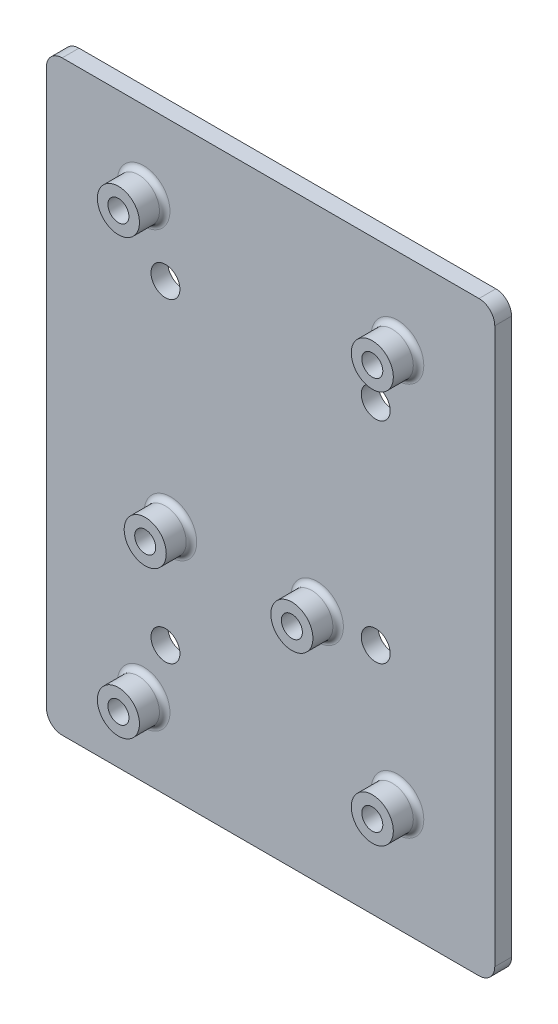
SolidWorks part; units mm, degrees
ref_plane "Front Plane" through (0, 0, 0) normal (0, 0, 1) x (1, 0, 0)
ref_plane "Top Plane" through (0, 0, 0) normal (0, 1, 0) x (1, 0, 0)
ref_plane "Right Plane" through (0, 0, 0) normal (1, 0, 0) x (0, 0, -1)
sketch "Sketch1" plane through (0, 0, 0) normal (0, 0, 1) x (1, 0, 0)
  line L0 (0, 0) -> (27.9, 0) construction
  line L1 (-5.1, 52) -> (43.2, 52) construction
  line L2 (43.2, 52) -> (45.7, 52) construction
  line L3 (27.9, 0) -> (27.9, -24.1) construction
  line L4 (27.9, -24.1) -> (43.2, -24.1) construction
  line L5 (0, 0) -> (0, -30.6) construction
  line L6 (0, -30.6) -> (-5.1, -30.6) construction
  line L7 (-7.6, 66) -> (45.7, 66)
  line L8 (45.7, 66) -> (45.7, -31.4737)
  line L9 (30.4, -35.6) -> (-2.6, -35.6) construction
  line L10 (-7.6, -33.1) -> (-7.6, 66)
  line L11 (-5.1, 52) -> (-5.1, -30.6) construction
  line L12 (43.2, -24.1) -> (43.2, 52) construction
  line L13 (-5.1, 52) -> (-7.6, 52) construction
  line L14 (-7.6, -33.1) -> (-5.1, -33.1)
  line L15 (-5.1, -33.1) -> (-2.6, -35.6)
  line L16 (-2.6, -35.6) -> (30.4, -35.6)
  line L17 (30.4, -35.6) -> (32.9, -33.1)
  line L18 (32.9, -33.1) -> (44.0737, -33.1)
  line L19 (44.0737, -33.1) -> (45.7, -31.4737)
  line L20 (-23.6, 67) -> (61.7, 67)
  line L21 (61.7, 67) -> (61.7, -44.6)
  line L22 (61.7, -44.6) -> (-23.6, -44.6)
  line L23 (-23.6, -44.6) -> (-23.6, 67)
  circle A0 centre (-5.1, 52) radius 2
  circle A1 centre (43.2, 50.7) radius 2
  circle A2 centre (0, 0) radius 2
  circle A3 centre (27.9, 0) radius 2
  circle A4 centre (-5.1, -30.6) radius 2
  circle A5 centre (43.2, -24.1) radius 2
  point P9 (43.2, 50.7)
  dimension "D11" = 4
  dimension "D17" = 1.3
  dimension "D22" = 4
  dimension "D23" = 4
  dimension "D1" = 53.3
  dimension "D2" = 101.6
  dimension "D3" = 14
  dimension "D4" = 2.5
  dimension "D5" = 5.1
  dimension "D6" = 2.5
  dimension "D7" = 24.1
  dimension "D8" = 52
  dimension "D9" = 27.9
  dimension "D10" = 5
  dimension "D12" = 5
  dimension "D13" = 45
  dimension "D14" = 2.5
  dimension "D15" = 33
  dimension "D16" = 2.3
  dimension "D18" = 1
  dimension "D19" = 16
  dimension "D20" = 16
  dimension "D21" = 9
extrude "Base Plate" add sketch "Sketch1" along normal blind 3.2 contours L18 L19 L8 L7 L10 L14 L15 L16 L17 A5 A4 A3 A2 A1 A0 | L23 L22 L21 L20 L19 L18 L17 L16 L15 L14 L10 L7 L8
sketch "Sketch2" plane through (0, 0, 3.2) normal (0, 0, 1) x (1, 0, 0)
  circle A0 centre (-5.1, 52) radius 4
  circle A1 centre (43.2, 50.7) radius 4
  circle A2 centre (27.9, 0) radius 4
  circle A3 centre (0, 0) radius 4
  circle A4 centre (-5.1, -30.6) radius 4
  circle A5 centre (43.2, -24.1) radius 4
  circle A6 centre (43.2, -24.1) radius 2 construction
  circle A7 centre (-5.1, -30.6) radius 2 construction
  circle A8 centre (0, 0) radius 2 construction
  circle A9 centre (27.9, 0) radius 2 construction
  circle A10 centre (43.2, 50.7) radius 2 construction
  circle A11 centre (-5.1, 52) radius 2 construction
  circle A12 centre (43.2, -24.1) radius 2
  circle A13 centre (-5.1, -30.6) radius 2
  circle A14 centre (0, 0) radius 2
  circle A15 centre (27.9, 0) radius 2
  circle A16 centre (43.2, 50.7) radius 2
  circle A17 centre (-5.1, 52) radius 2
  dimension "D1" = 8
extrude "InsertStandoffs" add sketch "Sketch2" along normal blind 4.8
sketch "Sketch3" plane through (0, 0, 3.2) normal (0, 0, 1) x (1, 0, 0)
  line L0 (-0.95, 40.05) -> (39.05, 40.05) construction
  line L1 (39.05, 0.05) -> (39.05, 40.05) construction
  line L2 (-0.95, 40.05) -> (-0.95, -19.95) construction
  line L3 (39.05, 23.9853) -> (61.7, 23.9853) construction
  line L4 (61.7, 67) -> (61.7, -44.6) construction
  line L5 (-23.6, 23.0918) -> (-0.95, 23.0918) construction
  line L6 (-23.6, -44.6) -> (-23.6, 67) construction
  line L7 (40.0485, 42.6123) -> (42.6311, 41.606) construction
  line L8 (40.0485, 42.6123) -> (41.7477, 46.973) construction
  line L9 (41.7477, 46.973) -> (44.7902, 45.7874) construction
  line L10 (-3.6477, -26.873) -> (1.0264, -28.6943) construction
  line L11 (-1.9485, -22.5123) -> (1.2979, -23.7774) construction
  line L12 (-1.9485, -22.5123) -> (-3.6477, -26.873) construction
  circle A0 centre (-0.95, 40.05) radius 2.75
  circle A1 centre (39.05, 40.05) radius 2.75
  circle A2 centre (39.05, 0.05) radius 2.75
  circle A3 centre (-0.95, -19.95) radius 2.75
  circle A4 centre (43.2, 50.7) radius 4 construction
  circle A5 centre (-5.1, -30.6) radius 4 construction
  circle A6 centre (-5.1, -30.6) radius 4 construction
  dimension "D3" = 5.5
  dimension "D1" = 40
  dimension "D2" = 40
  dimension "D4" = 60
extrude "MountHoles" cut sketch "Sketch3" against normal through all both and the other way through all
fillet "Fillet1" radius 3 4 edges at (61.7, -44.6, 1.6) (-23.6, -44.6, 1.6) (61.7, 67, 1.6) (-23.6, 67, 1.6)
fillet "Fillet2" radius 1 6 edges at (-1.1, 52, 3.2) (47.2, 50.7, 3.2) (47.2, -24.1, 3.2) (31.9, 0, 3.2) (4, 0, 3.2) (-1.1, -30.6, 3.2)
sketch "SocketHeadClearance" plane through (0, 0, 3.2) normal (0, 0, 1) x (1, 0, 0)
  circle A0 centre (-0.95, -19.95) radius 6
  circle A1 centre (39.05, 40.05) radius 6
  circle A2 centre (39.05, 0.05) radius 6
  dimension "D1" = 12
  dimension "D2" = 12
  dimension "D3" = 12
